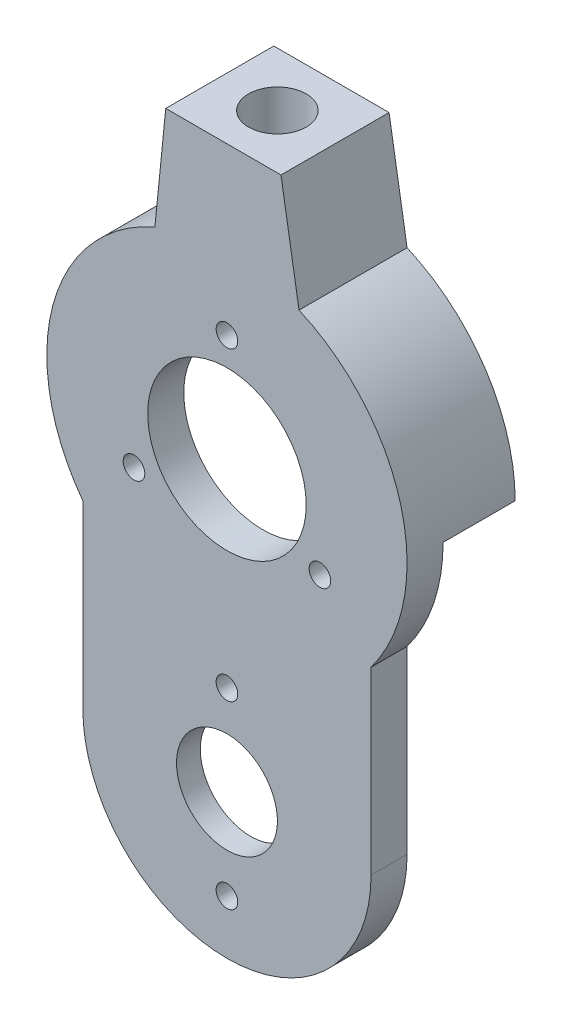
SolidWorks part; units mm, degrees
ref_plane "Front Plane" through (0, 0, 0) normal (0, 0, 1) x (1, 0, 0)
ref_plane "Top Plane" through (0, 0, 0) normal (0, 1, 0) x (1, 0, 0)
ref_plane "Right Plane" through (0, 0, 0) normal (1, 0, 0) x (0, 0, -1)
sketch "Sketch1" plane through (0, 0, 0) normal (0, 0, 1) x (1, 0, 0)
  line L1 (-20, -40) -> (20, -40)
  line L2 (-20, -40) -> (-20, 40)
  line L3 (-20, 40) -> (20, 40)
  line L4 (20, -40) -> (20, 40)
  line L5 (-20, -40) -> (20, 40) construction
  line L6 (-20, 40) -> (20, -40) construction
  point P0 (0, 0)
  dimension "D1" = 40
  dimension "D2" = 80
extrude "Boss-Extrude1" add sketch "Sketch1" along normal blind 5
sketch "Sketch2" plane through (0, 0, 5) normal (0, 0, 1) x (1, 0, 0)
  line L0 (20, 40) -> (-20, 40) construction
  line L1 (20, -40) -> (20, 40) construction
  circle A0 centre (0, 20) radius 11
  dimension "D1" = 22
  dimension "D2" = 20
  dimension "D3" = 20
extrude "Cut-Extrude1" cut sketch "Sketch2" against normal up to surface (5 mm away) up to face at (0, 0, 0)
sketch "Sketch3" plane through (0, 0, 0) normal (0, 0, -1) x (-1, 0, 0)
  line L0 (0, 34.9) -> (0, 0) construction
  line L1 (0, 20) -> (12.9038, 12.55) construction
  line L2 (-12.9038, 12.55) -> (0, 20) construction
  circle A0 centre (0, 34.9) radius 1.5
  circle A1 centre (12.9038, 12.55) radius 1.5
  circle A2 centre (-12.9038, 12.55) radius 1.5
  circle A3 centre (0, 20) radius 11 construction
  dimension "D1" = 3
  dimension "D2" = 3
  dimension "D3" = 3
  dimension "D6" = 14.9
  dimension "D4" = 14.9
  dimension "D5" = 120
  dimension "D7" = 120
  dimension "D8" = 14.9
extrude "Cut-Extrude2" cut sketch "Sketch3" against normal up to surface (5 mm away) up to face at (11, 20, 5)
sketch "Sketch4" plane through (0, 0, 0) normal (0, 0, -1) x (-1, 0, 0)
  line L0 (20, 40) -> (20, -40) construction
  circle A0 centre (0, -7.5) radius 1.5
  circle A1 centre (0, -32.5) radius 1.5
  dimension "D2" = 3
  dimension "D3" = 3
  dimension "D4" = 25
  dimension "D5" = 7.5
  dimension "D6" = 20
  dimension "D1" = 20
extrude "Cut-Extrude3" cut sketch "Sketch4" against normal up to surface (5 mm away) up to face at (-1.5, 34.9, 5)
sketch "Sketch6" plane through (0, 0, 0) normal (0, 0, -1) x (-1, 0, 0)
  line L0 (0, -7.5) -> (0, -32.5) construction
  circle A0 centre (0, -20) radius 19
  dimension "D1" = 38
extrude "Cut-Extrude4" cut sketch "Sketch6" against normal blind 1.7
sketch "Sketch7" plane through (0, 0, 1.7) normal (0, 0, -1) x (-1, 0, 0)
  circle A0 centre (0, -20) radius 7
  dimension "D1" = 14
extrude "Cut-Extrude5" cut sketch "Sketch7" against normal through all
sketch "Sketch8" plane through (0, 0, 0) normal (0, 0, -1) x (-1, 0, 0)
  line L0 (-20, 40) -> (20, 40) construction
  line L1 (-20, -40) -> (-20, 40) construction
  line L2 (-20, 20) -> (-20, 40)
  line L3 (20, 40) -> (20, -40) construction
  line L4 (20, 40) -> (20, 20)
  line L5 (-20, 40) -> (20, 40)
  line L6 (20, -40) -> (-20, -40) construction
  line L7 (-20, -40) -> (20, -40)
  line L8 (20, -40) -> (20, -20)
  line L10 (-20, -40) -> (-20, -20)
  arc A0 (20, 20) -> (-20, 20) centre (0, 20) ccw
  arc A1 (-20, -20) -> (20, -20) centre (0, -20) ccw
  line M8 (-20, 40) -> (-20, -40)
  line M9 (-20, -40) -> (20, -40)
  line M10 (20, -40) -> (20, 40)
  line M11 (20, 40) -> (-20, 40)
  dimension "D1" = 20
  dimension "D4" = 20
  dimension "D5" = 20
  dimension "D2" = 20
  dimension "D3" = 20
extrude "Cut-Extrude6" cut sketch "Sketch8" against normal through all contours A0 L5 M8 | A0 M10 M11 | A1 M8 M9 | A1 L7 M10
sketch "Sketch9" plane through (0, 0, 0) normal (0, 0, -1) x (-1, 0, 0)
  line L0 (20, 20) -> (20, -20) construction
  line L1 (-20, -20) -> (-20, 20) construction
  line L2 (20, 20) -> (20, 5)
  line L3 (-20, 5) -> (-20, 20)
  arc A0 (20, 5) -> (-20, 5) centre (0, 20) ccw
  arc A1 (20, 20) -> (-20, 20) centre (0, 20) ccw construction
  arc A2 (20, 20) -> (-20, 20) centre (0, 20) ccw
  dimension "D1" = 50
extrude "Boss-Extrude2" add sketch "Sketch9" against normal blind 5
sketch "Sketch10" plane through (0, 0, 0) normal (0, 0, -1) x (-1, 0, 0)
  line L0 (20, 20) -> (25, 20)
  line L1 (-20, 20) -> (-25, 20)
  arc A0 (25, 20) -> (-25, 20) centre (0, 20) ccw
  arc A1 (20, 20) -> (-20, 20) centre (0, 20) ccw
  dimension "D1" = 50
  dimension "D2" = 40
extrude "Boss-Extrude3" add sketch "Sketch10" along normal blind 10
sketch "Sketch11" plane through (0, 0, -10) normal (0, 0, -1) x (-1, 0, 0)
  line L0 (-10, 42.9129) -> (-7.5, 57.9129)
  line L1 (-7.5, 57.9129) -> (8.5, 57.9129)
  line L2 (8.5, 57.9129) -> (10, 42.9129)
  line L3 (10, 42.9129) -> (-10, 42.9129)
  arc A0 (25, 20) -> (-25, 20) centre (0, 20) ccw construction
  circle A1 centre (0, 20) radius 11 construction
  dimension "D4" = 15
  dimension "D1" = 10
  dimension "D2" = 7.5
  dimension "D3" = 16
extrude "Boss-Extrude4" add sketch "Sketch11" against normal up to surface (15 mm away) up to face at (0, -2.5, 5)
sketch "Sketch12" plane through (0, 57.9129, 0) normal (0, 1, 0) x (1, 0, 0)
  line L0 (-8.5, 10) -> (7.5, 10) construction
  line L1 (7.5, -5) -> (7.5, 10) construction
  circle A0 centre (-0.5, 2.5) radius 3
  dimension "D1" = 6
  dimension "D2" = 7.5
  dimension "D3" = 8
extrude "Cut-Extrude7" cut sketch "Sketch12" against normal blind 15
sketch "Sketch13" plane through (0, 57.9129, 0) normal (0, 1, 0) x (1, 0, 0)
  circle A0 centre (-0.5, 2.5) radius 4
  dimension "D1" = 8
extrude "Cut-Extrude8" cut sketch "Sketch13" against normal blind 15
